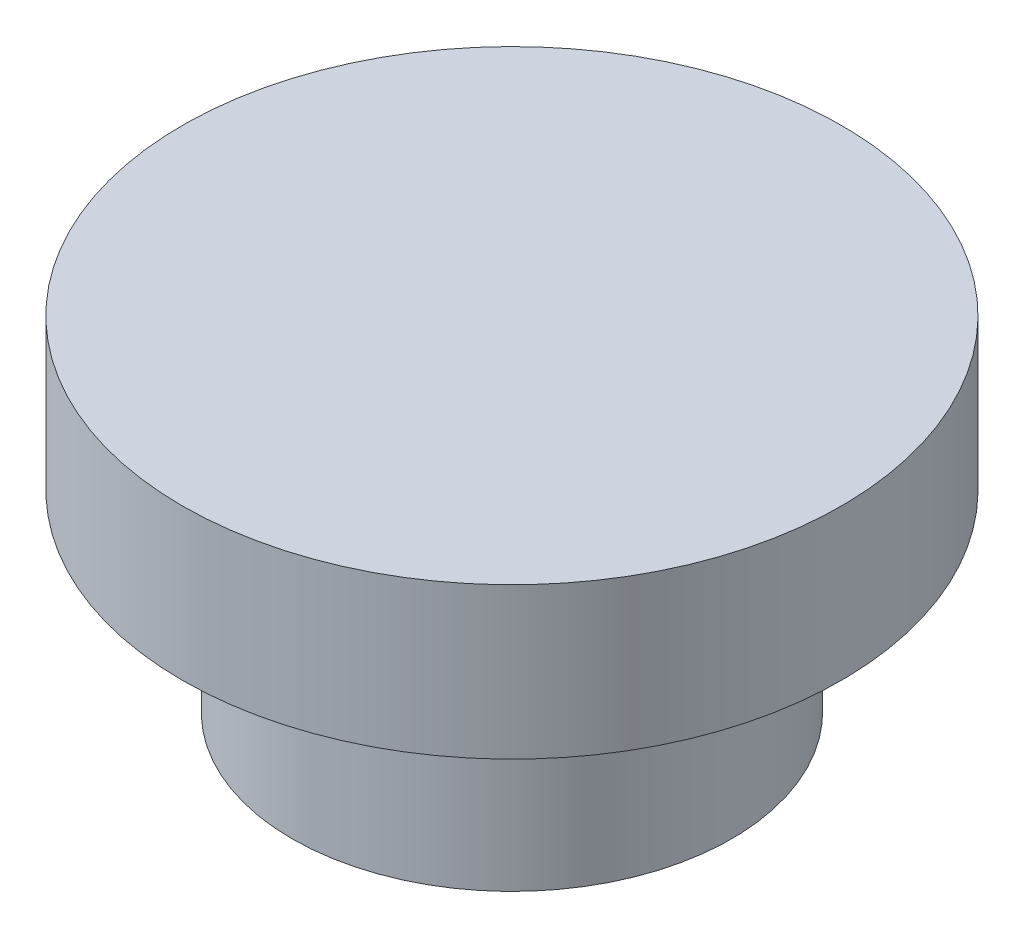
SolidWorks part; units mm, degrees
ref_plane "Front Plane" through (0, 0, 0) normal (0, 0, 1) x (1, 0, 0)
ref_plane "Top Plane" through (0, 0, 0) normal (0, 1, 0) x (1, 0, 0)
ref_plane "Right Plane" through (0, 0, 0) normal (1, 0, 0) x (0, 0, -1)
sketch "Sketch2" plane through (0, 0, 0) normal (0, 1, 0) x (1, 0, 0)
  circle A0 centre (0, 0) radius 50.8
  dimension "D1" = 101.6
extrude "InjectorMan" add sketch "Sketch2" along normal blind 50.8
sketch "Sketch3" plane through (0, 50.8, 0) normal (0, 1, 0) x (1, 0, 0)
  circle A0 centre (0, 0) radius 44.1201
  circle A1 centre (0, 0) radius 38.5365
extrude "OxMan1" cut sketch "Sketch3" against normal blind 44.45
sketch "Sketch4" plane through (0, 50.8, 0) normal (0, 1, 0) x (1, 0, 0)
  circle A0 centre (0, 0) radius 30.48
  circle A1 centre (0, 0) radius 25.4
  dimension "D1" = 50.8
  dimension "D2" = 60.96
extrude "FuelMan" cut sketch "Sketch4" against normal blind 44.45
sketch "Sketch5" plane through (0, 50.8, 0) normal (0, 1, 0) x (1, 0, 0)
  circle A0 centre (0, 0) radius 18.4579
  circle A1 centre (0, 0) radius 13.3359
extrude "OxMan2" cut sketch "Sketch5" against normal blind 44.45
sketch "Sketch6" plane through (0, 50.8, 0) normal (0, 1, 0) x (1, 0, 0)
  line L0 (-76.2, 0) -> (76.2, 0) construction
  line L1 (-69.85, -1.905) -> (-59.69, -1.905)
  line L2 (-69.85, -1.905) -> (-69.85, 1.905)
  line L3 (-69.85, 1.905) -> (-59.69, 1.905)
  line L4 (-59.69, -1.905) -> (-59.69, 1.905)
  line L5 (-69.0676, 10.5978) -> (-59.0709, 8.7837)
  line L6 (-69.0676, 10.5978) -> (-68.3873, 14.3466)
  line L7 (-68.3873, 14.3466) -> (-58.3906, 12.5324)
  line L8 (-59.0709, 8.7837) -> (-58.3906, 12.5324)
  line L9 (-66.0654, 22.76) -> (-56.5532, 19.19)
  line L10 (-66.0654, 22.76) -> (-64.7266, 26.3271)
  line L11 (-64.7266, 26.3271) -> (-55.2145, 22.7571)
  line L12 (-56.5532, 19.19) -> (-55.2145, 22.7571)
  line L13 (-60.9397, 34.1907) -> (-52.2179, 28.9796)
  line L14 (-60.9397, 34.1907) -> (-58.9856, 37.4614)
  line L15 (-58.9856, 37.4614) -> (-50.2637, 32.2503)
  line L16 (-52.2179, 28.9796) -> (-50.2637, 32.2503)
  line L17 (-53.8554, 44.5224) -> (-46.2042, 37.8378)
  line L18 (-53.8554, 44.5224) -> (-51.3487, 47.3916)
  line L19 (-51.3487, 47.3916) -> (-43.6975, 40.707)
  line L20 (-46.2042, 37.8378) -> (-43.6975, 40.707)
  line L21 (-45.0402, 53.4232) -> (-38.7055, 45.4798)
  line L22 (-45.0402, 53.4232) -> (-42.0614, 55.7987)
  line L23 (-42.0614, 55.7987) -> (-35.7267, 47.8553)
  line L24 (-38.7055, 45.4798) -> (-35.7267, 47.8553)
  line L25 (-34.7773, 60.6069) -> (-29.9628, 51.66)
  line L26 (-34.7773, 60.6069) -> (-31.4222, 62.4123)
  line L27 (-31.4222, 62.4123) -> (-26.6077, 53.4655)
  line L28 (-29.9628, 51.66) -> (-26.6077, 53.4655)
  line L29 (-23.3966, 65.8426) -> (-20.257, 56.1799)
  line L30 (-23.3966, 65.8426) -> (-19.7731, 67.02)
  line L31 (-19.7731, 67.02) -> (-16.6335, 57.3572)
  line L32 (-20.257, 56.1799) -> (-16.6335, 57.3572)
  line L33 (-11.264, 68.9621) -> (-9.9001, 58.8941)
  line L34 (-11.264, 68.9621) -> (-7.4884, 69.4736)
  line L35 (-7.4884, 69.4736) -> (-6.1246, 59.4055)
  line L36 (-9.9001, 58.8941) -> (-6.1246, 59.4055)
  line L37 (1.2307, 69.8651) -> (0.7749, 59.7154)
  line L38 (1.2307, 69.8651) -> (5.0369, 69.6942)
  line L39 (5.0369, 69.6942) -> (4.5811, 59.5444)
  line L40 (0.7749, 59.7154) -> (4.5811, 59.5444)
  line L41 (13.6858, 68.5226) -> (11.425, 58.6173)
  line L42 (13.6858, 68.5226) -> (17.4003, 67.6748)
  line L43 (17.4003, 67.6748) -> (15.1395, 57.7695)
  line L44 (11.425, 58.6173) -> (15.1395, 57.7695)
  line L45 (25.7011, 64.9777) -> (21.708, 55.6353)
  line L46 (25.7011, 64.9777) -> (29.2045, 63.4803)
  line L47 (29.2045, 63.4803) -> (25.2114, 54.1379)
  line L48 (21.708, 55.6353) -> (25.2114, 54.1379)
  line L49 (36.8903, 59.3444) -> (31.2932, 50.8651)
  line L50 (36.8903, 59.3444) -> (40.07, 57.2455)
  line L51 (40.07, 57.2455) -> (34.4729, 48.7662)
  line L52 (31.2932, 50.8651) -> (34.4729, 48.7662)
  line L53 (46.8938, 51.8037) -> (39.8726, 44.4601)
  line L54 (46.8938, 51.8037) -> (49.6477, 49.1707)
  line L55 (49.6477, 49.1707) -> (42.6265, 41.8272)
  line L56 (39.8726, 44.4601) -> (42.6265, 41.8272)
  line L57 (55.3901, 42.598) -> (47.1705, 36.6261)
  line L58 (55.3901, 42.598) -> (57.6296, 39.5156)
  line L59 (57.6296, 39.5156) -> (49.41, 33.5437)
  line L60 (47.1705, 36.6261) -> (49.41, 33.5437)
  line L61 (62.1061, 32.0231) -> (52.9523, 27.6149)
  line L62 (62.1061, 32.0231) -> (63.7592, 28.5904)
  line L63 (63.7592, 28.5904) -> (54.6054, 24.1822)
  line L64 (52.9523, 27.6149) -> (54.6054, 24.1822)
  line L65 (66.826, 20.419) -> (57.0321, 17.7161)
  line L66 (66.826, 20.419) -> (67.8396, 16.7463)
  line L67 (67.8396, 16.7463) -> (58.0457, 14.0434)
  line L68 (57.0321, 17.7161) -> (58.0457, 14.0434)
  line L69 (69.398, 8.1586) -> (59.2789, 7.2479)
  line L70 (69.398, 8.1586) -> (69.7396, 4.364)
  line L71 (69.7396, 4.364) -> (59.6205, 3.4532)
  line L72 (59.2789, 7.2479) -> (59.6205, 3.4532)
  line L73 (69.7396, -4.364) -> (59.6205, -3.4532)
  line L74 (69.7396, -4.364) -> (69.398, -8.1586)
  line L75 (69.398, -8.1586) -> (59.2789, -7.2479)
  line L76 (59.6205, -3.4532) -> (59.2789, -7.2479)
  line L77 (67.8396, -16.7463) -> (58.0457, -14.0434)
  line L78 (67.8396, -16.7463) -> (66.826, -20.419)
  line L79 (66.826, -20.419) -> (57.0321, -17.7161)
  line L80 (58.0457, -14.0434) -> (57.0321, -17.7161)
  line L81 (63.7592, -28.5904) -> (54.6054, -24.1822)
  line L82 (63.7592, -28.5904) -> (62.1061, -32.0231)
  line L83 (62.1061, -32.0231) -> (52.9523, -27.6149)
  line L84 (54.6054, -24.1822) -> (52.9523, -27.6149)
  line L85 (57.6296, -39.5156) -> (49.41, -33.5437)
  line L86 (57.6296, -39.5156) -> (55.3901, -42.598)
  line L87 (55.3901, -42.598) -> (47.1705, -36.6261)
  line L88 (49.41, -33.5437) -> (47.1705, -36.6261)
  line L89 (49.6477, -49.1707) -> (42.6265, -41.8272)
  line L90 (49.6477, -49.1707) -> (46.8938, -51.8037)
  line L91 (46.8938, -51.8037) -> (39.8726, -44.4601)
  line L92 (42.6265, -41.8272) -> (39.8726, -44.4601)
  line L93 (40.07, -57.2455) -> (34.4729, -48.7662)
  line L94 (40.07, -57.2455) -> (36.8903, -59.3444)
  line L95 (36.8903, -59.3444) -> (31.2932, -50.8651)
  line L96 (34.4729, -48.7662) -> (31.2932, -50.8651)
  line L97 (29.2045, -63.4803) -> (25.2114, -54.1379)
  line L98 (29.2045, -63.4803) -> (25.7011, -64.9777)
  line L99 (25.7011, -64.9777) -> (21.708, -55.6353)
  line L100 (25.2114, -54.1379) -> (21.708, -55.6353)
  line L101 (17.4003, -67.6748) -> (15.1395, -57.7695)
  line L102 (17.4003, -67.6748) -> (13.6858, -68.5226)
  line L103 (13.6858, -68.5226) -> (11.425, -58.6173)
  line L104 (15.1395, -57.7695) -> (11.425, -58.6173)
  line L105 (5.0369, -69.6942) -> (4.5811, -59.5444)
  line L106 (5.0369, -69.6942) -> (1.2307, -69.8651)
  line L107 (1.2307, -69.8651) -> (0.7749, -59.7154)
  line L108 (4.5811, -59.5444) -> (0.7749, -59.7154)
  line L109 (-7.4884, -69.4736) -> (-6.1246, -59.4055)
  line L110 (-7.4884, -69.4736) -> (-11.264, -68.9621)
  line L111 (-11.264, -68.9621) -> (-9.9001, -58.8941)
  line L112 (-6.1246, -59.4055) -> (-9.9001, -58.8941)
  line L113 (-19.7731, -67.02) -> (-16.6335, -57.3572)
  line L114 (-19.7731, -67.02) -> (-23.3966, -65.8426)
  line L115 (-23.3966, -65.8426) -> (-20.257, -56.1799)
  line L116 (-16.6335, -57.3572) -> (-20.257, -56.1799)
  line L117 (-31.4222, -62.4123) -> (-26.6077, -53.4655)
  line L118 (-31.4222, -62.4123) -> (-34.7773, -60.6069)
  line L119 (-34.7773, -60.6069) -> (-29.9628, -51.66)
  line L120 (-26.6077, -53.4655) -> (-29.9628, -51.66)
  line L121 (-42.0614, -55.7987) -> (-35.7267, -47.8553)
  line L122 (-42.0614, -55.7987) -> (-45.0402, -53.4232)
  line L123 (-45.0402, -53.4232) -> (-38.7055, -45.4798)
  line L124 (-35.7267, -47.8553) -> (-38.7055, -45.4798)
  line L125 (-51.3487, -47.3916) -> (-43.6975, -40.707)
  line L126 (-51.3487, -47.3916) -> (-53.8554, -44.5224)
  line L127 (-53.8554, -44.5224) -> (-46.2042, -37.8378)
  line L128 (-43.6975, -40.707) -> (-46.2042, -37.8378)
  line L129 (-58.9856, -37.4614) -> (-50.2637, -32.2503)
  line L130 (-58.9856, -37.4614) -> (-60.9397, -34.1907)
  line L131 (-60.9397, -34.1907) -> (-52.2179, -28.9796)
  line L132 (-50.2637, -32.2503) -> (-52.2179, -28.9796)
  line L133 (-64.7266, -26.3271) -> (-55.2145, -22.7571)
  line L134 (-64.7266, -26.3271) -> (-66.0654, -22.76)
  line L135 (-66.0654, -22.76) -> (-56.5532, -19.19)
  line L136 (-55.2145, -22.7571) -> (-56.5532, -19.19)
  line L137 (-68.3873, -14.3466) -> (-58.3906, -12.5324)
  line L138 (-68.3873, -14.3466) -> (-69.0676, -10.5978)
  line L139 (-69.0676, -10.5978) -> (-59.0709, -8.7837)
  line L140 (-58.3906, -12.5324) -> (-59.0709, -8.7837)
  circle A0 centre (0, 0) radius 76.2
  point P7 (-59.69, 0)
  point P10 (0, 0)
  point P150 (0, 0)
  dimension "D1" = 3.81
  dimension "D4" = 152.4
  dimension "D2" = 10.16
  dimension "D3" = 6.35
  dimension "D5" = 35
extrude "RegenDist" add sketch "Sketch6" along normal blind 25.4
sketch "Sketch7" plane through (0, 76.2, 0) normal (0, 1, 0) x (1, 0, 0)
  circle A0 centre (0, 0) radius 76.2
  circle A1 centre (0, 0) radius 69.85
  dimension "D1" = 152.4
  dimension "D2" = 139.7
extrude "RegenToFuelMan" add sketch "Sketch7" along normal blind 6.35
sketch "Sketch8" plane through (0, 82.55, 0) normal (0, 1, 0) x (1, 0, 0)
  circle A0 centre (0, 0) radius 76.2
extrude "FuelManLid" add sketch "Sketch8" along normal blind 3.175
sketch "Sketch10" plane through (0, 76.2, 0) normal (0, 1, 0) x (1, 0, 0)
  circle A0 centre (0, 0) radius 30.48
  circle A1 centre (0, 0) radius 25.4
  dimension "D1" = 50.8
  dimension "D2" = 60.96
extrude "Cut-Extrude4" cut sketch "Sketch10" against normal blind 25.4
sketch "Sketch11" plane through (0, 0, 0) normal (0, -1, 0) x (1, 0, 0)
  circle A0 centre (0, 0) radius 50.8
extrude "Cut-Extrude5" cut sketch "Sketch11" against normal blind 6.35
equation "\"diameter\"= 4"
equation "\"t\"=2"
